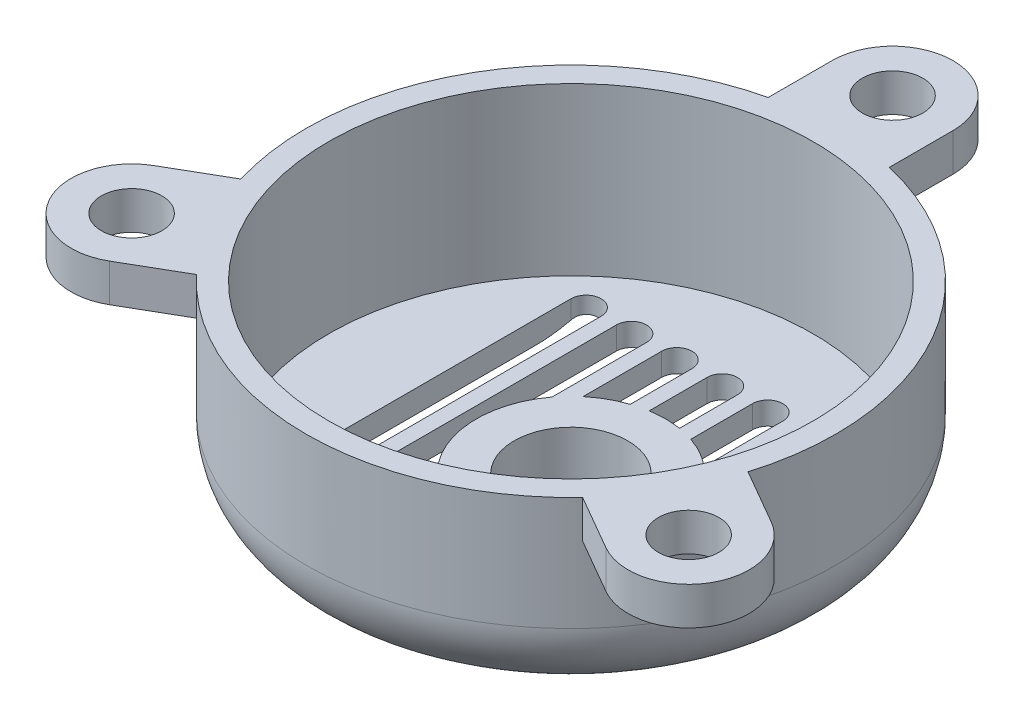
SolidWorks part; units mm, degrees
ref_plane "Front Plane" through (0, 0, 0) normal (0, 0, 1) x (1, 0, 0)
ref_plane "Top Plane" through (0, 0, 0) normal (0, 1, 0) x (1, 0, 0)
ref_plane "Right Plane" through (0, 0, 0) normal (1, 0, 0) x (0, 0, -1)
sketch "Sketch1" plane through (0, 0, 0) normal (0, 1, 0) x (1, 0, 0)
  circle A0 centre (0, 0) radius 35
  dimension "D1" = 70
extrude "Boss-Extrude1" add sketch "Sketch1" along normal blind 25
shell "Shell1" thickness 3
fillet "Fillet1" radius 10 1 edges at (0, 0, 35)
sketch "Sketch4" plane through (0, 25, 0) normal (0, 1, 0) x (1, 0, 0)
  line L1 (-8, 27.5) -> (8, 27.5)
  line L2 (-8, 27.5) -> (-8, 42.5)
  line L4 (8, 27.5) -> (8, 42.5)
  line L5 (-8, 27.5) -> (8, 42.5) construction
  line L6 (-8, 42.5) -> (8, 27.5) construction
  circle A0 centre (0, 0) radius 35 construction
  arc A1 (-0.5156, 34.5166) -> (0.5156, 34.5166) centre (0, 42.5) ccw
  circle A2 centre (0, 42.5) radius 4
  arc A3 (8, 42.5) -> (-8, 42.5) centre (0, 42.5) ccw
  point P0 (0, 35)
  circle M2 centre (0, 0) radius 35
  dimension "D1" = 8
  dimension "D2" = 16
  dimension "D3" = 42.5
extrude "Boss-Extrude2" add sketch "Sketch4" against normal blind 5 contours L4 A3 L2 A2 M2
pattern_circular "CirPattern1" count 3 over 360 about axis through (0, 0, 0) along (0, 1, 0) of "Boss-Extrude2"
sketch "Sketch5" plane through (0, 0, 0) normal (0, -1, 0) x (1, 0, 0)
  line L0 (-18, 20) -> (-18, -20) construction
  line L1 (-16, 20) -> (-16, -20)
  line L2 (-20, 20) -> (-20, -20)
  line L3 (0, 0) -> (15.9701, 0)
  line L4 (-12, 20) -> (-12, -20) construction
  line L5 (-10, 20) -> (-10, -20)
  line L6 (-14, 20) -> (-14, -20)
  line L7 (-6, 20) -> (-6, -20) construction
  line L8 (-4, 20) -> (-4, -20)
  line L9 (-8, 20) -> (-8, -20)
  line L10 (0, 20) -> (0, -20) construction
  line L11 (2, 20) -> (2, -20)
  line L12 (-2, 20) -> (-2, -20)
  line L13 (6, 20) -> (6, -20) construction
  line L14 (8, 20) -> (8, -20)
  line L15 (4, 20) -> (4, -20)
  line L16 (12, 20) -> (12, -20) construction
  line L17 (14, 20) -> (14, -20)
  line L18 (10, 20) -> (10, -20)
  line L19 (18, 20) -> (18, -20) construction
  line L20 (20, 20) -> (20, -20)
  line L21 (16, 20) -> (16, -20)
  arc A0 (-16, 20) -> (-20, 20) centre (-18, 20) ccw
  arc A1 (-20, -20) -> (-16, -20) centre (-18, -20) ccw
  arc A2 (-10, 20) -> (-14, 20) centre (-12, 20) ccw
  arc A3 (-14, -20) -> (-10, -20) centre (-12, -20) ccw
  arc A4 (-4, 20) -> (-8, 20) centre (-6, 20) ccw
  arc A5 (-8, -20) -> (-4, -20) centre (-6, -20) ccw
  arc A6 (2, 20) -> (-2, 20) centre (0, 20) ccw
  arc A7 (-2, -20) -> (2, -20) centre (0, -20) ccw
  arc A8 (8, 20) -> (4, 20) centre (6, 20) ccw
  arc A9 (4, -20) -> (8, -20) centre (6, -20) ccw
  arc A10 (14, 20) -> (10, 20) centre (12, 20) ccw
  arc A11 (10, -20) -> (14, -20) centre (12, -20) ccw
  arc A12 (20, 20) -> (16, 20) centre (18, 20) ccw
  arc A13 (16, -20) -> (20, -20) centre (18, -20) ccw
  point P2 (-18, 0)
  point P14 (-12, 0)
  point P21 (-6, 0)
  point P28 (0, 0)
  point P35 (6, 0)
  point P42 (12, 0)
  point P49 (18, 0)
  dimension "D1" = 2
  dimension "D2" = 40
  dimension "D3" = 18
  dimension "D4" = 7
extrude "Cut-Extrude1" cut sketch "Sketch5" against normal through all contours L6 A3 L5 A2 | L8 A5 L9 A4 | L11 A7 L12 A6 | L2 A1 L1 A0 | L20 A13 L21 A12 | L18 A11 L17 A10 | L15 A9 L14 A8
sketch "Sketch7" plane through (0, 0, 0) normal (0, -1, 0) x (1, 0, 0)
  circle A0 centre (0, 0) radius 12.5
  dimension "D1" = 25
extrude "Boss-Extrude3" add sketch "Sketch7" along normal blind 5 and the other way blind 3
fillet "Fillet2" radius 2 1 edges at (0, -5, -12.5)
sketch "Sketch8" plane through (0, -5, 0) normal (0, -1, 0) x (1, 0, 0)
  circle A0 centre (0, 0) radius 7.5
  dimension "D1" = 15
extrude "Cut-Extrude2" cut sketch "Sketch8" against normal through all
